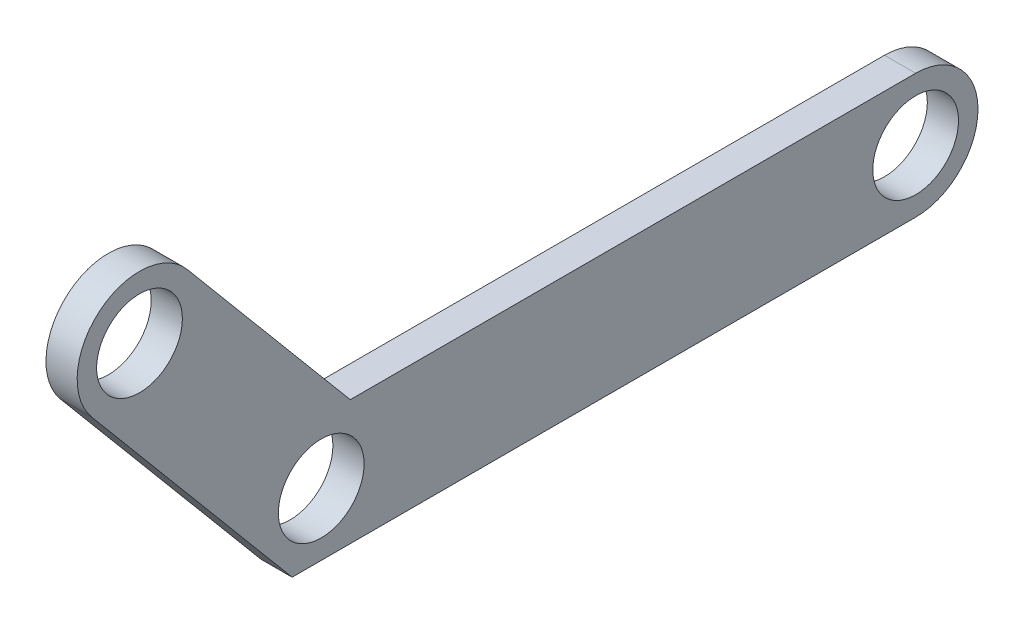
SolidWorks part; units mm, degrees
ref_plane "Front Plane" through (0, 0, 0) normal (0, 0, 1) x (1, 0, 0)
ref_plane "Top Plane" through (0, 0, 0) normal (0, 1, 0) x (1, 0, 0)
ref_plane "Right Plane" through (0, 0, 0) normal (1, 0, 0) x (0, 0, -1)
sketch "Sketch1" plane through (0, 0, 0) normal (1, 0, 0) x (0, 0, -1)
  line L0 (0, 0) -> (-12.8558, 15.3209)
  line L1 (0, 0) -> (40, 0)
  line L3 (3.7305, 8) -> (40, 8)
  line L6 (-6.7274, 20.4632) -> (3.7305, 8)
  line L8 (-12.3627, 20.9562) -> (5.2216, 0) construction
  line L9 (44, 4) -> (-3.3564, 4) construction
  line L10 (3.7305, 8) -> (0, 0) construction
  circle A0 centre (-9.7916, 17.892) radius 2.75
  circle A1 centre (40, 4) radius 2.75
  circle A2 centre (1.8652, 4) radius 2.75
  arc A3 (-6.7274, 20.4632) -> (-12.8558, 15.3209) centre (-9.7916, 17.892) ccw
  arc A4 (40, 0) -> (40, 8) centre (40, 4) ccw
  dimension "D1" = 5.5
  dimension "D5" = 5.5
  dimension "D6" = 40
  dimension "D7" = 130
  dimension "D8" = 5.5
  dimension "D10" = 1.25
  dimension "D9" = 1.25
  dimension "D2" = 8
  dimension "D3" = 8
  dimension "D4" = 20
extrude "Boss-Extrude1" add sketch "Sketch1" along normal blind 2
